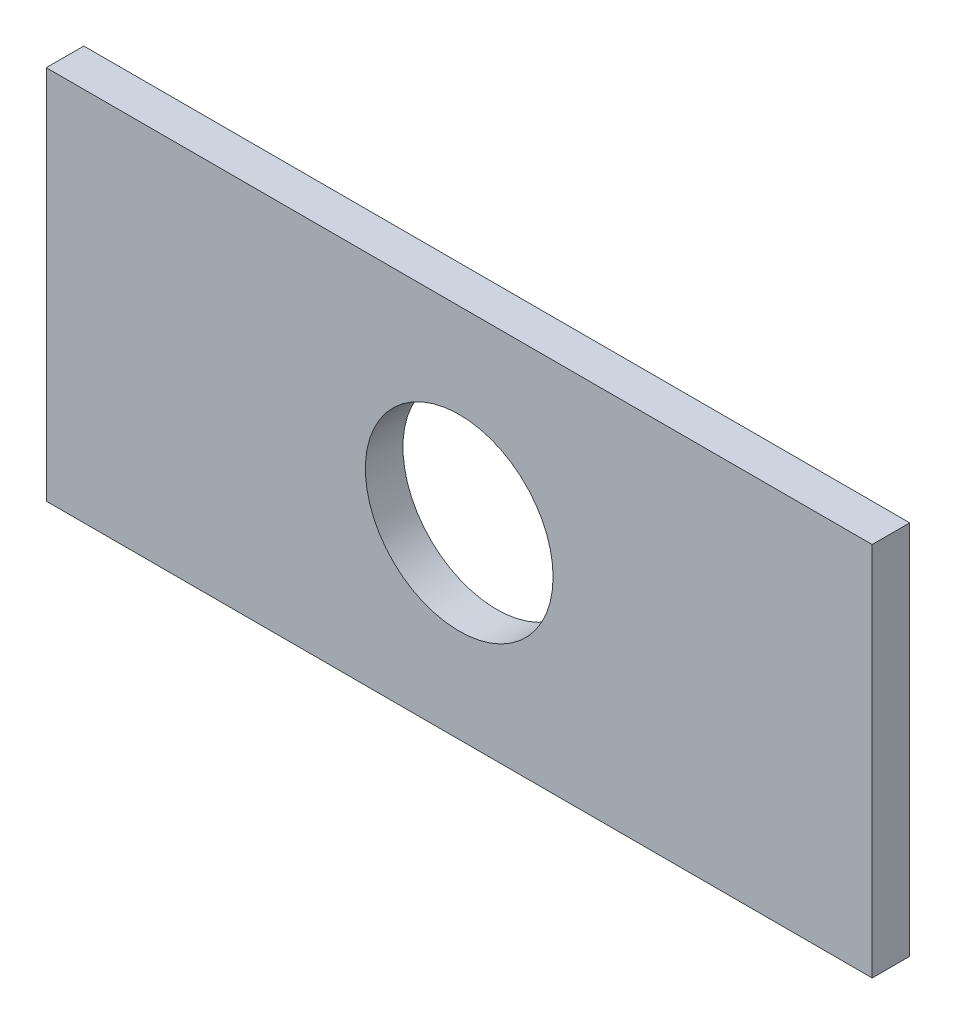
SolidWorks part; units mm, degrees
ref_plane "Front Plane" through (0, 0, 0) normal (0, 0, 1) x (1, 0, 0)
ref_plane "Top Plane" through (0, 0, 0) normal (0, 1, 0) x (1, 0, 0)
ref_plane "Right Plane" through (0, 0, 0) normal (1, 0, 0) x (0, 0, -1)
sketch "Sketch1" plane through (0, 0, 0) normal (0, 0, 1) x (1, 0, 0)
  line L0 (-50.1451, 10.4446) -> (-39.1451, 10.4446)
  line L1 (-39.1451, 10.4446) -> (-39.1451, 5.4446)
  line L2 (-39.1451, 5.4446) -> (-50.1451, 5.4446)
  line L3 (-50.1451, 5.4446) -> (-50.1451, 10.4446)
  circle A0 centre (-44.6451, 7.9446) radius 1.25
  point P0 (-50.1451, 7.9446)
  point P1 (-44.6451, 10.4446)
  dimension "D2" = 2.5
  dimension "D3" = 5
  dimension "D1" = 11
extrude "Boss-Extrude1" add sketch "Sketch1" along normal blind 0.5
scale "Scale2" scale about origin uniform scaling yes scale factor 5
